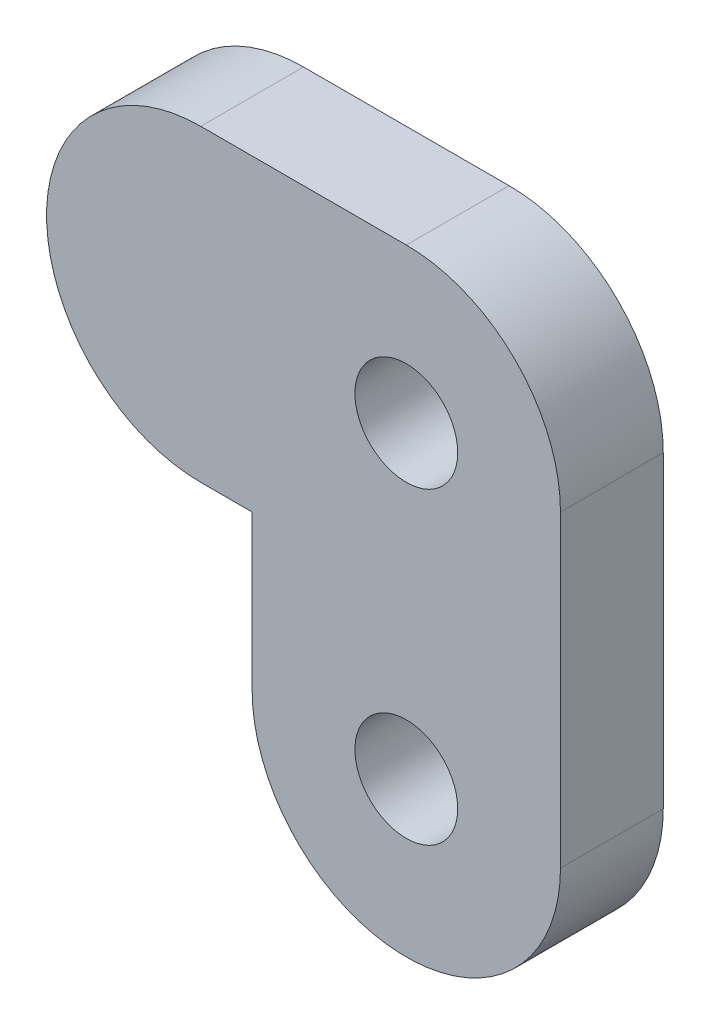
SolidWorks part; units mm, degrees
ref_plane "Alzado" through (0, 0, 0) normal (0, 0, 1) x (1, 0, 0)
ref_plane "Planta" through (0, 0, 0) normal (0, 1, 0) x (1, 0, 0)
ref_plane "Vista lateral" through (0, 0, 0) normal (1, 0, 0) x (0, 0, -1)
sketch "Model" plane through (0, 0, 0) normal (0, 0, 1) x (1, 0, 0)
  line L0 (152.3421, 211.824) -> (158.3421, 211.824)
  line L1 (153.8421, 202.824) -> (152.3421, 202.824)
  line L2 (162.8421, 198.324) -> (162.8421, 207.324)
  line L3 (153.8421, 198.324) -> (153.8421, 202.824)
  arc A0 (152.3421, 211.824) -> (152.3421, 202.824) centre (152.3421, 207.324) ccw
  arc A1 (162.8421, 207.324) -> (158.3421, 211.824) centre (158.3421, 207.324) ccw
  circle A2 centre (158.3421, 207.324) radius 1.5
  arc A3 (153.8421, 198.324) -> (162.8421, 198.324) centre (158.3421, 198.324) ccw
  circle A4 centre (158.3421, 198.324) radius 1.5
extrude "Saliente-Extruir1" add sketch "Model" along normal blind 3
